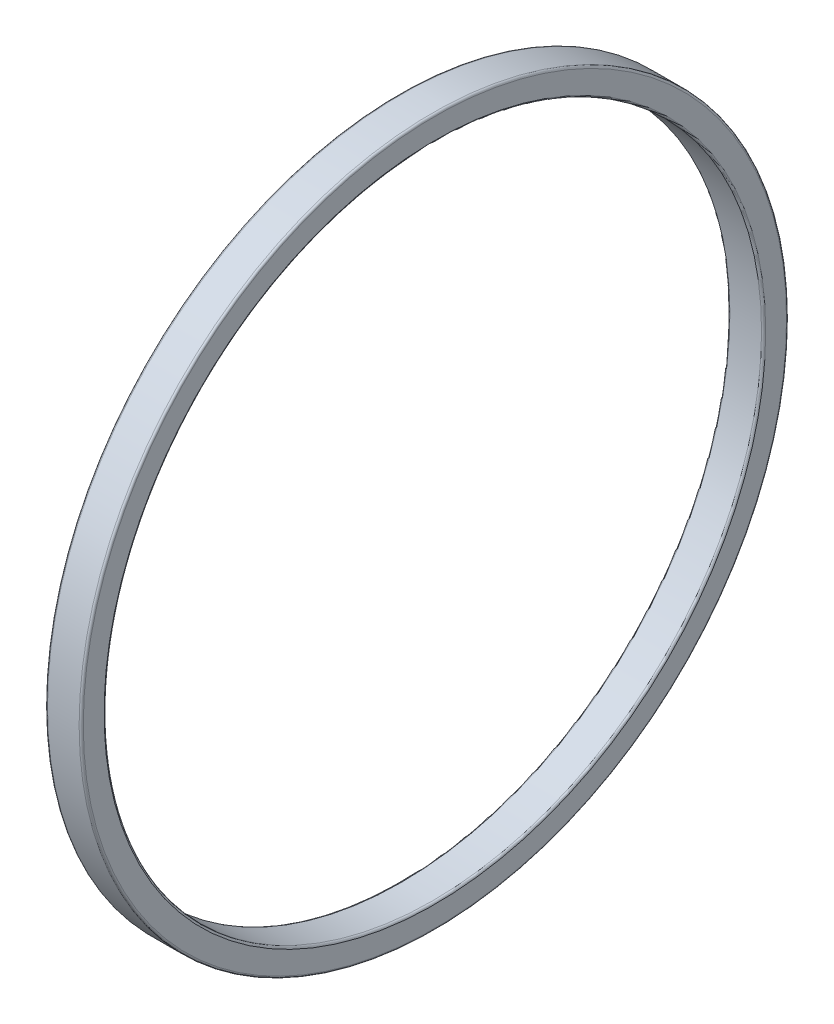
SolidWorks part; units mm, degrees
ref_plane "Front Plane" through (0, 0, 0) normal (0, 0, 1) x (1, 0, 0)
ref_plane "Top Plane" through (0, 0, 0) normal (0, 1, 0) x (1, 0, 0)
ref_plane "Right Plane" through (0, 0, 0) normal (1, 0, 0) x (0, 0, -1)
sketch "Sketch1" plane through (0, 0, 0) normal (1, 0, 0) x (0, 0, -1)
  circle A0 centre (0, 0) radius 42.5
  circle A1 centre (0, 0) radius 39.5
  dimension "D1" = 79
  dimension "D2" = 85
extrude "Boss-Extrude1" add sketch "Sketch1" along normal mid plane 4.3
fillet "Fillet1" radius 0.25 4 edges at (-2.15, 0, -42.5) (2.15, 0, -42.5) (-2.15, 0, -39.5) (2.15, 0, -39.5)
